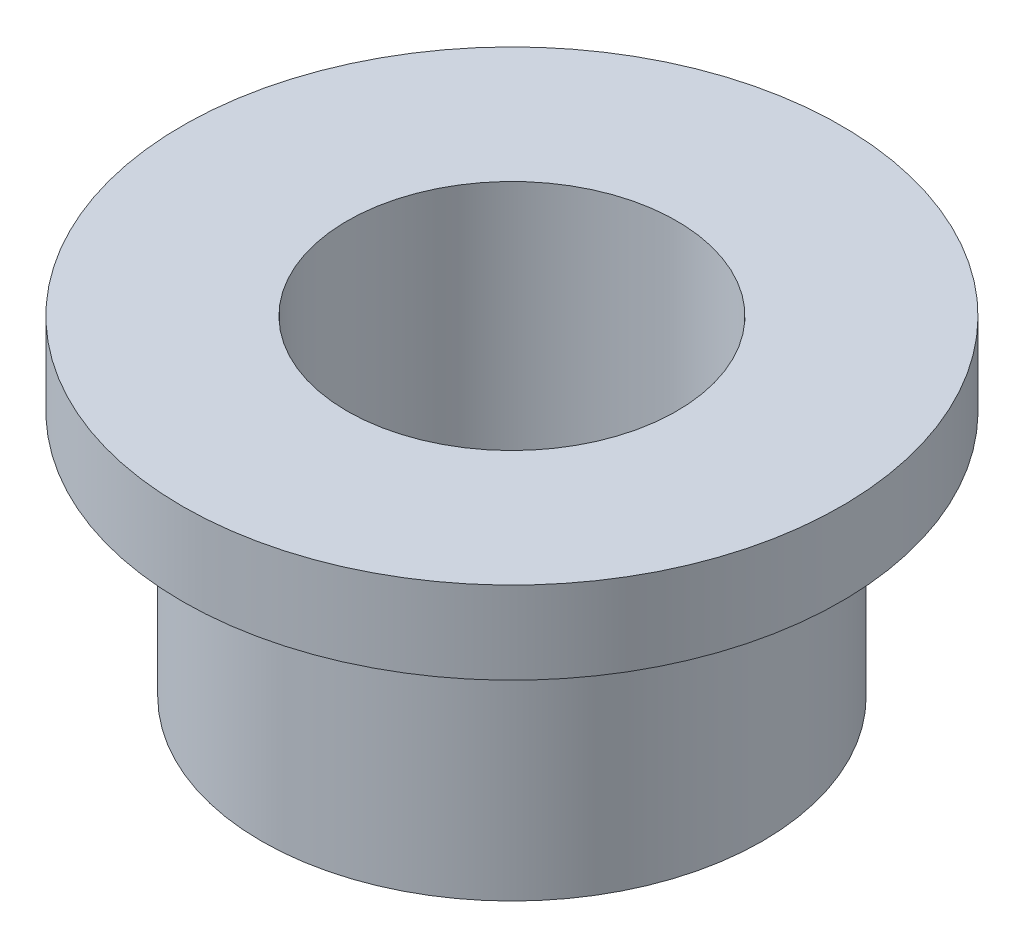
SolidWorks part; units mm, degrees
material "Brass"
ref_plane "Front Plane" through (0, 0, 0) normal (0, 0, 1) x (1, 0, 0)
ref_plane "Top Plane" through (0, 0, 0) normal (0, 1, 0) x (1, 0, 0)
ref_plane "Right Plane" through (0, 0, 0) normal (1, 0, 0) x (0, 0, -1)
sketch "Sketch1" plane through (0, 0, 0) normal (0, 1, 0) x (1, 0, 0)
  circle A0 centre (0, 0) radius 4.826
  circle A1 centre (0, 0) radius 3.175
extrude "Boss-Extrude1" add sketch "Sketch1" along normal blind 6.35
sketch "Sketch2" plane through (0, 6.35, 0) normal (0, 1, 0) x (1, 0, 0)
  circle A0 centre (0, 0) radius 6.35
  circle A1 centre (0, 0) radius 4.826
extrude "Boss-Extrude2" add sketch "Sketch2" against normal blind 1.5875
